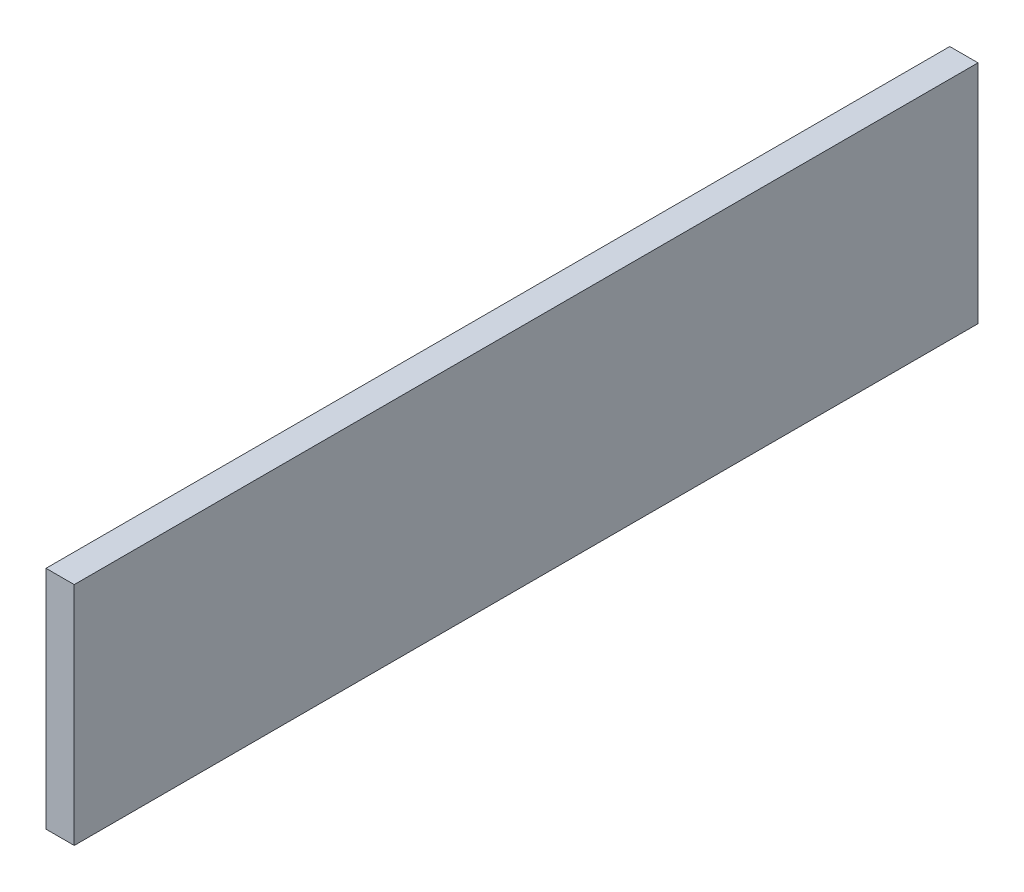
SolidWorks part; units mm, degrees
ref_plane "Front Plane" through (0, 0, 0) normal (0, 0, 1) x (1, 0, 0)
ref_plane "Top Plane" through (0, 0, 0) normal (0, 1, 0) x (1, 0, 0)
ref_plane "Right Plane" through (0, 0, 0) normal (1, 0, 0) x (0, 0, -1)
sketch "Sketch1" plane through (0, 0, 0) normal (0, 0, 1) x (1, 0, 0)
  line L1 (0, 0) -> (6.35, 0)
  line L2 (0, 0) -> (0, 50.8)
  line L3 (0, 50.8) -> (6.35, 50.8)
  line L4 (6.35, 0) -> (6.35, 50.8)
  dimension "D1" = 50.8
  dimension "D2" = 6.35
extrude "Boss-Extrude1" add sketch "Sketch1" along normal blind 203.2
